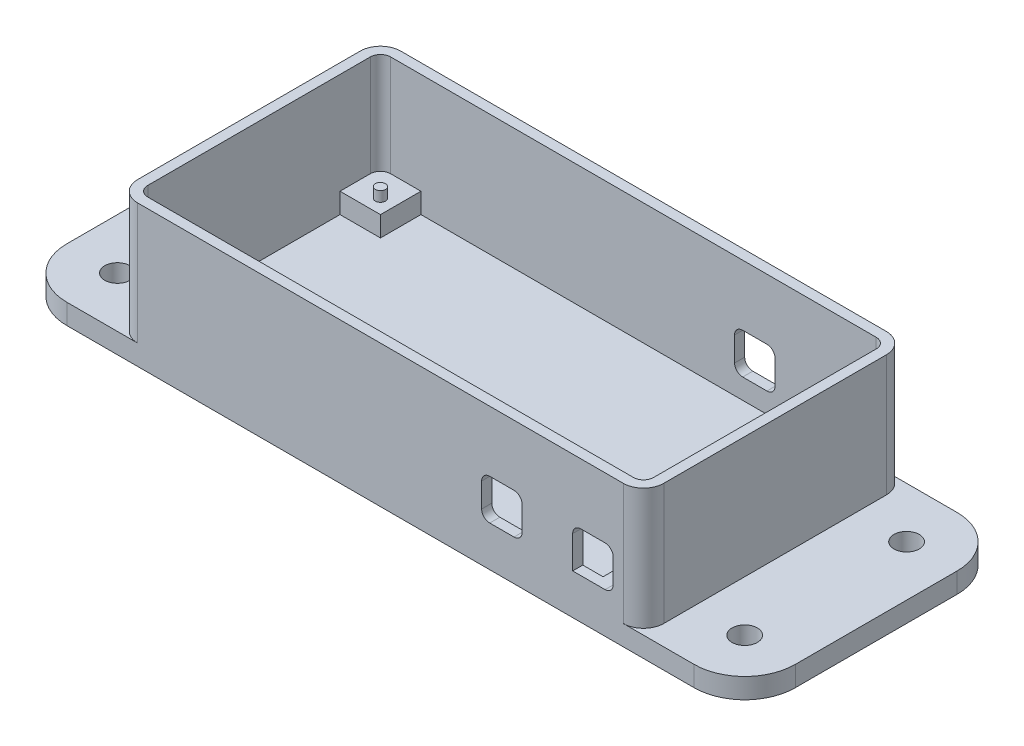
SolidWorks part; units mm, degrees
ref_plane "Front Plane" through (0, 0, 0) normal (0, 0, 1) x (1, 0, 0)
ref_plane "Top Plane" through (0, 0, 0) normal (0, 1, 0) x (1, 0, 0)
ref_plane "Right Plane" through (0, 0, 0) normal (1, 0, 0) x (0, 0, -1)
sketch "Sketch1" plane through (0, 0, 0) normal (0, 1, 0) x (1, 0, 0)
  line L1 (0, 0) -> (-182.88, 0)
  line L2 (0, 0) -> (0, 66.04)
  line L3 (0, 66.04) -> (-182.88, 66.04)
  line L4 (-182.88, 0) -> (-182.88, 66.04)
  dimension "D1" = 182.88
  dimension "D2" = 66.04
extrude "Boss-Extrude2" add sketch "Sketch1" along normal blind 5.08
fillet "Fillet2" radius 12.7 4 edges at (0, 2.54, -66.04) (0, 2.54, 0) (-182.88, 2.54, 0) (-182.88, 2.54, -66.04)
sketch "Sketch3" plane through (0, 5.08, 0) normal (0, 1, 0) x (1, 0, 0)
  line L0 (-91.44, 0) -> (-91.44, 66.04) construction
  line L1 (-170.18, 0) -> (-12.7, 0) construction
  line L2 (-12.7, 66.04) -> (-170.18, 66.04) construction
  circle A0 centre (-12.7, 12.7) radius 3.175
  circle A1 centre (-12.7, 53.34) radius 3.175
  circle A2 centre (-170.18, 53.34) radius 3.175
  circle A3 centre (-170.18, 12.7) radius 3.175
  dimension "D1" = 6.35
  dimension "D2" = 6.35
extrude "Cut-Extrude1" cut sketch "Sketch3" against normal through all both and the other way through all
sketch "Sketch4" plane through (0, 5.08, 0) normal (0, 1, 0) x (1, 0, 0)
  line L0 (-91.44, 2.54) -> (-91.44, 63.5) construction
  line L1 (-170.18, 0) -> (-12.7, 0) construction
  line L2 (-30.6064, 0) -> (-157.48, 0)
  line L3 (-25.4, 0) -> (-25.4, 66.04)
  line L4 (-25.4, 66.04) -> (-157.48, 66.04)
  line L5 (-157.48, 0) -> (-157.48, 66.04)
  line L6 (-12.7, 66.04) -> (-170.18, 66.04) construction
  line L7 (-182.88, 53.34) -> (-182.88, 12.7) construction
  line L8 (-27.94, 10.16) -> (-35.56, 10.16)
  line L9 (-27.94, 2.54) -> (-154.94, 2.54)
  line L10 (-27.94, 2.54) -> (-27.94, 63.5)
  line L11 (-27.94, 63.5) -> (-154.94, 63.5)
  line L12 (-154.94, 2.54) -> (-154.94, 63.5)
  line L13 (-35.56, 10.16) -> (-35.56, 2.54)
  line L14 (-27.94, 33.02) -> (-154.94, 33.02) construction
  line L15 (-147.32, 10.16) -> (-147.32, 2.54)
  line L16 (-154.94, 10.16) -> (-147.32, 10.16)
  line L17 (-154.94, 55.88) -> (-147.32, 55.88)
  line L18 (-147.32, 55.88) -> (-147.32, 63.5)
  line L19 (-35.56, 55.88) -> (-35.56, 63.5)
  line L20 (-27.94, 55.88) -> (-35.56, 55.88)
  line M15 (-12.7, 66.04) -> (-170.18, 66.04)
  line M19 (-170.18, 0) -> (-12.7, 0)
  dimension "D1" = 132.08
  dimension "D2" = 25.4
  dimension "D3" = 60.96
  dimension "D4" = 2.54
  dimension "D5" = 127
  dimension "D6" = 2.54
  dimension "D7" = 7.62
  dimension "D8" = 7.62
extrude "Boss-Extrude6" add sketch "Sketch4" along normal blind 30.48 contours L5 L3 L9 L12 L11 L10 M19 M15
sketch "Sketch7" plane through (0, 5.08, 0) normal (0, 1, 0) x (1, 0, 0)
  line L0 (-91.44, 2.54) -> (-91.44, 63.5) construction
  line L1 (-27.94, 2.54) -> (-38.1, 2.54)
  line L2 (-27.94, 2.54) -> (-27.94, 12.7)
  line L3 (-27.94, 12.7) -> (-38.1, 12.7)
  line L4 (-38.1, 2.54) -> (-38.1, 12.7)
  line L5 (-27.94, 2.54) -> (-154.94, 2.54) construction
  line L6 (-27.94, 63.5) -> (-154.94, 63.5) construction
  line L7 (-27.94, 33.02) -> (-154.94, 33.02) construction
  line L8 (-27.94, 2.54) -> (-27.94, 63.5) construction
  line L9 (-154.94, 2.54) -> (-154.94, 63.5) construction
  line L10 (-144.78, 2.54) -> (-144.78, 12.7)
  line L11 (-154.94, 12.7) -> (-144.78, 12.7)
  line L12 (-154.94, 2.54) -> (-154.94, 12.7)
  line L13 (-154.94, 2.54) -> (-144.78, 2.54)
  line L14 (-154.94, 63.5) -> (-144.78, 63.5)
  line L15 (-154.94, 63.5) -> (-154.94, 53.34)
  line L16 (-154.94, 53.34) -> (-144.78, 53.34)
  line L17 (-144.78, 63.5) -> (-144.78, 53.34)
  line L18 (-38.1, 63.5) -> (-38.1, 53.34)
  line L19 (-27.94, 53.34) -> (-38.1, 53.34)
  line L20 (-27.94, 63.5) -> (-27.94, 53.34)
  line L21 (-27.94, 63.5) -> (-38.1, 63.5)
  dimension "D1" = 10.16
  dimension "D2" = 10.16
extrude "Boss-Extrude8" add sketch "Sketch7" along normal blind 5.08
sketch "Sketch10" plane through (0, 10.16, 0) normal (0, 1, 0) x (1, 0, 0)
  line L0 (-38.1, 2.54) -> (-27.94, 2.54) construction
  line L2 (-27.94, 2.54) -> (-27.94, 12.7) construction
  line L3 (-154.94, 2.54) -> (-144.78, 2.54) construction
  line L4 (-154.94, 12.7) -> (-154.94, 2.54) construction
  line L5 (-154.94, 63.5) -> (-154.94, 53.34) construction
  line L6 (-144.78, 63.5) -> (-154.94, 63.5) construction
  line L9 (-27.94, 63.5) -> (-38.1, 63.5) construction
  line L10 (-27.94, 53.34) -> (-27.94, 63.5) construction
  circle A0 centre (-34.544, 9.144) radius 1.27
  circle A1 centre (-148.336, 9.144) radius 1.27
  circle A2 centre (-148.336, 56.896) radius 1.27
  circle A3 centre (-34.544, 56.896) radius 1.27
  dimension "D1" = 2.54
  dimension "D4" = 2.54
  dimension "D7" = 2.54
  dimension "D10" = 2.54
  dimension "D2" = 6.604
  dimension "D3" = 6.604
  dimension "D5" = 6.604
  dimension "D6" = 6.604
  dimension "D8" = 6.604
  dimension "D9" = 6.604
  dimension "D11" = 6.604
  dimension "D12" = 6.604
extrude "Boss-Extrude10" add sketch "Sketch10" along normal blind 2.54
sketch "Sketch12" plane through (0, 0, -66.04) normal (0, 0, -1) x (-1, 0, 0)
  line L0 (25.4, 35.56) -> (25.4, 5.08) construction
  line L1 (33.02, 20.32) -> (43.18, 20.32)
  line L2 (33.02, 20.32) -> (33.02, 10.16)
  line L3 (33.02, 10.16) -> (43.18, 10.16)
  line L4 (43.18, 20.32) -> (43.18, 10.16)
  line L6 (55.88, 20.32) -> (66.04, 20.32)
  line L7 (55.88, 20.32) -> (55.88, 10.16)
  line L8 (55.88, 10.16) -> (66.04, 10.16)
  line L9 (66.04, 20.32) -> (66.04, 10.16)
  dimension "D1" = 7.62
  dimension "D2" = 17.78
  dimension "D3" = 5.08
  dimension "D4" = 15.24
  dimension "D5" = 12.7
  dimension "D6" = 10.16
extrude "Cut-Extrude4" cut sketch "Sketch12" against normal up to next and the other way through all
sketch "Sketch14" plane through (0, 0, 0) normal (0, 0, 1) x (1, 0, 0)
  line L1 (-43.18, 20.32) -> (-33.02, 20.32)
  line L2 (-43.18, 20.32) -> (-43.18, 10.16)
  line L3 (-43.18, 10.16) -> (-33.02, 10.16)
  line L4 (-33.02, 20.32) -> (-33.02, 10.16)
  line L5 (-66.04, 20.32) -> (-55.88, 20.32)
  line L6 (-66.04, 20.32) -> (-66.04, 10.16)
  line L7 (-66.04, 10.16) -> (-55.88, 10.16)
  line L8 (-55.88, 20.32) -> (-55.88, 10.16)
  dimension "D1" = 7.62
  dimension "D2" = 10.16
  dimension "D3" = 12.7
  dimension "D4" = 10.16
  dimension "D5" = 5.08
  dimension "D6" = 10.16
extrude "Cut-Extrude5" cut sketch "Sketch14" against normal up to next
fillet "Fillet5" radius 2.032 15 edges at (-33.02, 10.16, -64.77) (-43.18, 10.16, -64.77) (-43.18, 20.32, -64.77) (-33.02, 20.32, -64.77) (-55.88, 10.16, -64.77) (-55.88, 20.32, -64.77) (-66.04, 20.32, -64.77) (-66.04, 10.16, -64.77) (-66.04, 10.16, -1.27) (-43.18, 20.32, -1.27) (-66.04, 20.32, -1.27) (-33.02, 20.32, -1.27) (-55.88, 20.32, -1.27) (-33.02, 10.16, -1.27) (-55.88, 10.16, -1.27)
fillet "Fillet6" radius 5.08 4 edges at (-25.4, 20.32, -66.04) (-25.4, 20.32, 0) (-157.48, 20.32, 0) (-157.48, 20.32, -66.04)
fillet "Fillet7" radius 2.54 4 edges at (-154.94, 22.86, -63.5) (-27.94, 22.86, -63.5) (-154.94, 22.86, -2.54) (-27.94, 22.86, -2.54)
